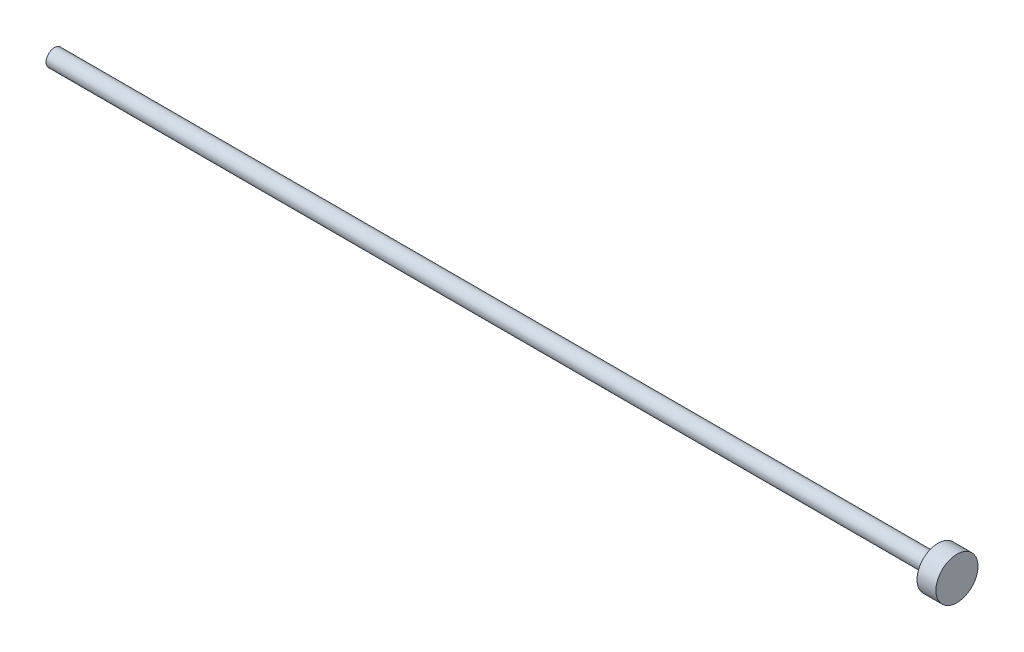
SolidWorks part; units mm, degrees
ref_plane "前视基准面" through (0, 0, 0) normal (0, 0, 1) x (1, 0, 0)
ref_plane "上视基准面" through (0, 0, 0) normal (0, 1, 0) x (1, 0, 0)
ref_plane "右视基准面" through (0, 0, 0) normal (1, 0, 0) x (0, 0, -1)
sketch "草图1" plane through (0, 0, 0) normal (1, 0, 0) x (0, 0, -1)
  circle A0 centre (0, 0) radius 5
  dimension "D1" = 10
extrude "凸台-拉伸1" add sketch "草图1" along normal blind 4.5
sketch "草图2" plane through (0, 0, 0) normal (-1, 0, 0) x (0, 0, 1)
  circle A0 centre (0, 0) radius 2
  dimension "D1" = 4
extrude "凸台-拉伸2" add sketch "草图2" along normal blind 210
